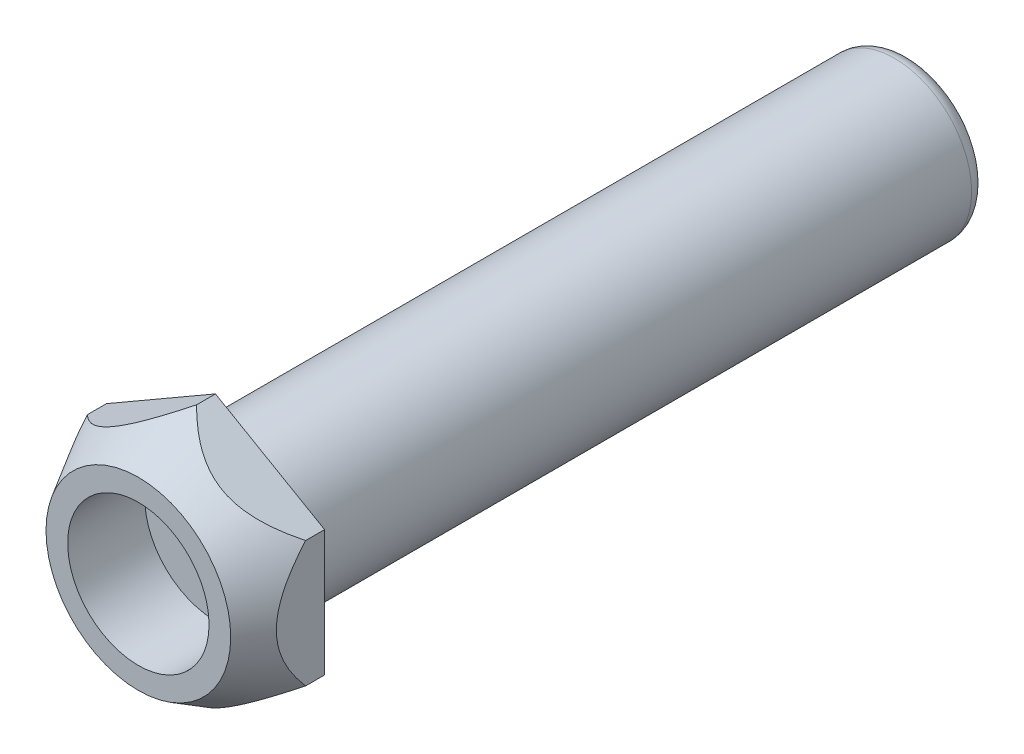
SolidWorks part; units mm, degrees
ref_plane "Front Plane" through (0, 0, 0) normal (0, 0, 1) x (1, 0, 0)
ref_plane "Top Plane" through (0, 0, 0) normal (0, 1, 0) x (1, 0, 0)
ref_plane "Right Plane" through (0, 0, 0) normal (1, 0, 0) x (0, 0, -1)
sketch "Sketch1" plane through (0, 0, 0) normal (0, 0, 1) x (1, 0, 0)
  circle A0 centre (0, 0) radius 1
  dimension "D1" = 2
extrude "Boss-Extrude1" add sketch "Sketch1" along normal blind 9
sketch "Sketch2" plane through (0, 0, 9) normal (0, 0, 1) x (1, 0, 0)
  line L1 (0, 1.6323) -> (-1.4136, 0.8162)
  line L2 (-1.4136, 0.8162) -> (-1.4136, -0.8162)
  line L3 (-1.4136, -0.8162) -> (0, -1.6323)
  line L4 (0, -1.6323) -> (1.4136, -0.8162)
  line L5 (1.4136, -0.8162) -> (1.4136, 0.8162)
  line L6 (1.4136, 0.8162) -> (0, 1.6323)
  circle A0 centre (0, 0) radius 1.4136 construction
extrude "Boss-Extrude2" add sketch "Sketch2" along normal blind 1
sketch "Sketch3" plane through (0, 0, 10) normal (0, 0, 1) x (1, 0, 0)
  circle A0 centre (0, 0) radius 0.9162
extrude "Cut-Extrude1" cut sketch "Sketch3" against normal blind 1
sketch "Sketch5" plane through (0, 0, 10) normal (0, 0, 1) x (1, 0, 0)
  circle A0 centre (0, 0) radius 1.197
extrude "Cut-Extrude3" cut sketch "Sketch5" against normal blind 1 draft 30 flip side to cut
fillet "Fillet1" radius 0.2 1 edges at (1, 0, 0)
